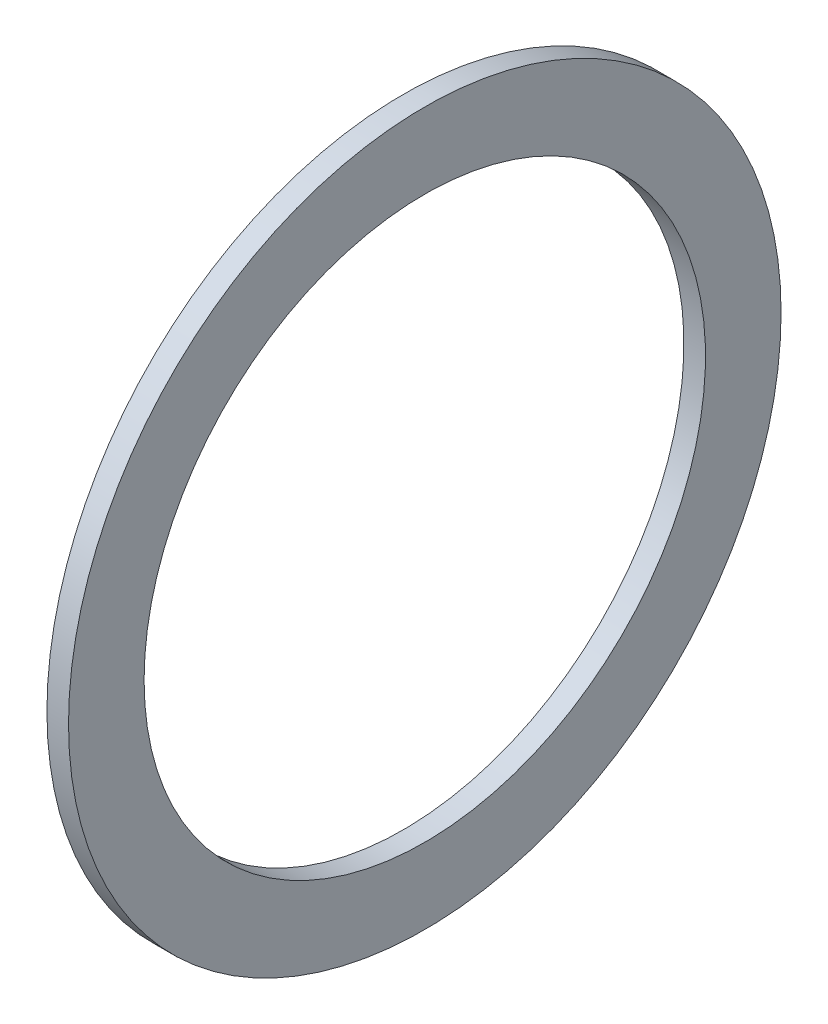
SolidWorks part; units mm, degrees
ref_plane "Front Plane" through (0, 0, 0) normal (0, 0, 1) x (1, 0, 0)
ref_plane "Top Plane" through (0, 0, 0) normal (0, 1, 0) x (1, 0, 0)
ref_plane "Right Plane" through (0, 0, 0) normal (1, 0, 0) x (0, 0, -1)
sketch "Axial profile (mm)" plane through (0, 0, 0) normal (0, 0, 1) x (1, 0, 0)
  line L0 (-110, 0) -> (75, 0) construction
  line L1 (0, 13) -> (1, 13)
  line L2 (1, 13) -> (1, 16.5)
  line L3 (1, 16.5) -> (0, 16.5)
  line L4 (0, 16.5) -> (0, 13)
revolve "Full revolution" add sketch "Axial profile (mm)" angle 360 about L0
